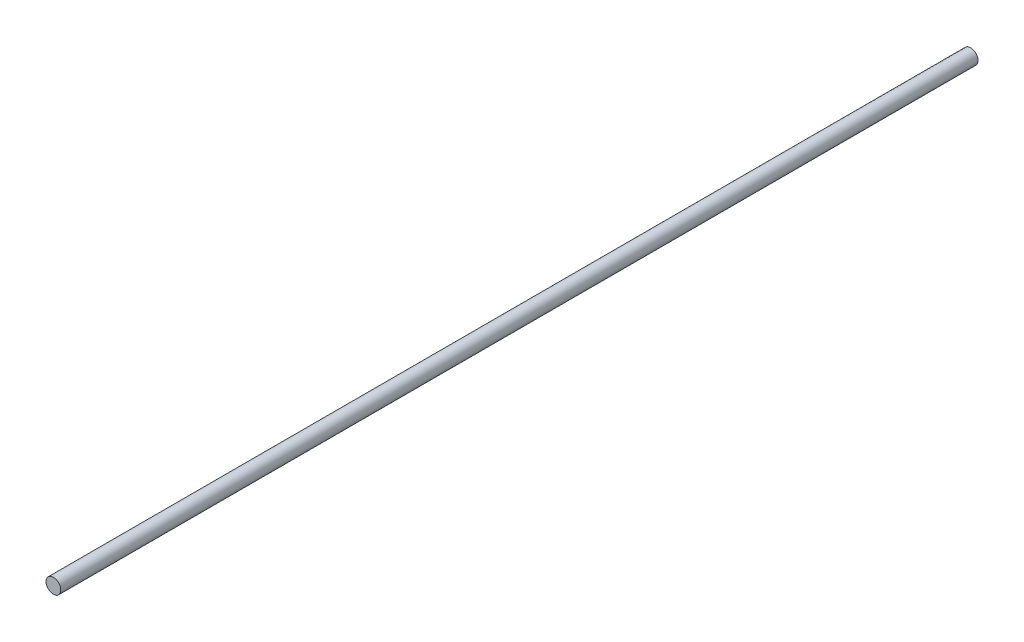
SolidWorks part; units mm, degrees
ref_plane "前视基准面" through (0, 0, 0) normal (0, 0, 1) x (1, 0, 0)
ref_plane "上视基准面" through (0, 0, 0) normal (0, 1, 0) x (1, 0, 0)
ref_plane "右视基准面" through (0, 0, 0) normal (1, 0, 0) x (0, 0, -1)
other "Configuration Table"
sketch "草图1" plane through (0, 0, 0) normal (0, 0, 1) x (1, 0, 0)
  circle A0 centre (0, 0) radius 2
  dimension "diameter" = 4
extrude "Cable_envelope" add sketch "草图1" along normal blind 248.7729
